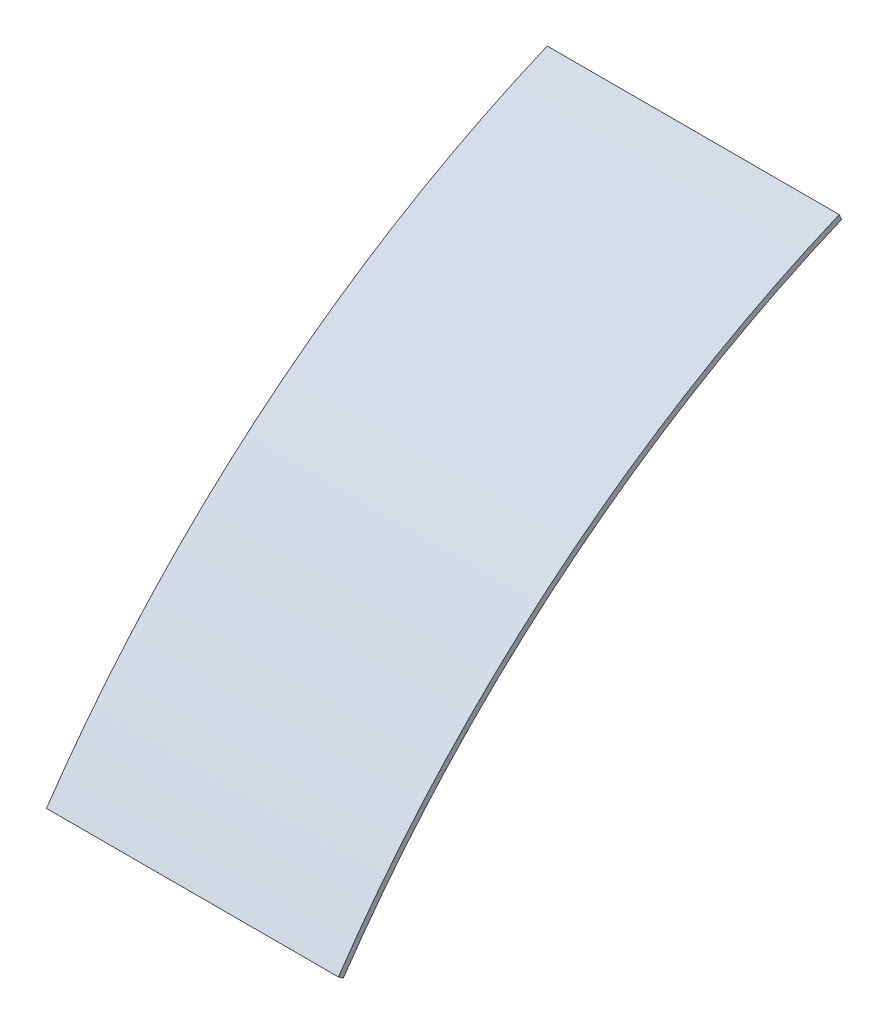
SolidWorks part; units mm, degrees
material "Acrylic (Medium-high impact)"
ref_plane "Front Plane" through (0, 0, 0) normal (0, 0, 1) x (1, 0, 0)
ref_plane "Top Plane" through (0, 0, 0) normal (0, 1, 0) x (1, 0, 0)
ref_plane "Right Plane" through (0, 0, 0) normal (1, 0, 0) x (0, 0, -1)
sketch "Sketch1" plane through (0, 0, 0) normal (1, 0, 0) x (0, 0, -1)
  line L0 (-248.2734, -206.9112) -> (-250.7508, -205.2242)
  line L5 (0, 0) -> (1.1642, -2.7619)
  arc A0 (0, 0) -> (-250.7508, -205.2242) centre (222.1754, -527.2628) ccw
  arc A1 (1.1642, -2.7619) -> (-248.2734, -206.9112) centre (222.1754, -527.2628) ccw
  arc A2 (0.5821, -1.3809) -> (-249.5121, -206.0677) centre (222.1754, -527.2628) ccw
  dimension "D3" = 570.6622
  dimension "D1" = 2.9972
  dimension "D2" = 327.66
extrude "Boss-Extrude1" add sketch "Sketch1" along normal blind 146.2024 contours L5 A2 L0 A1 | A2 L5 A0 L0
equation "\"WallThickness\"=0.118"
equation "\"D1\"= \"WallThickness\""
equation "\"D1@Sketch1\"=\"WallThickness\""
